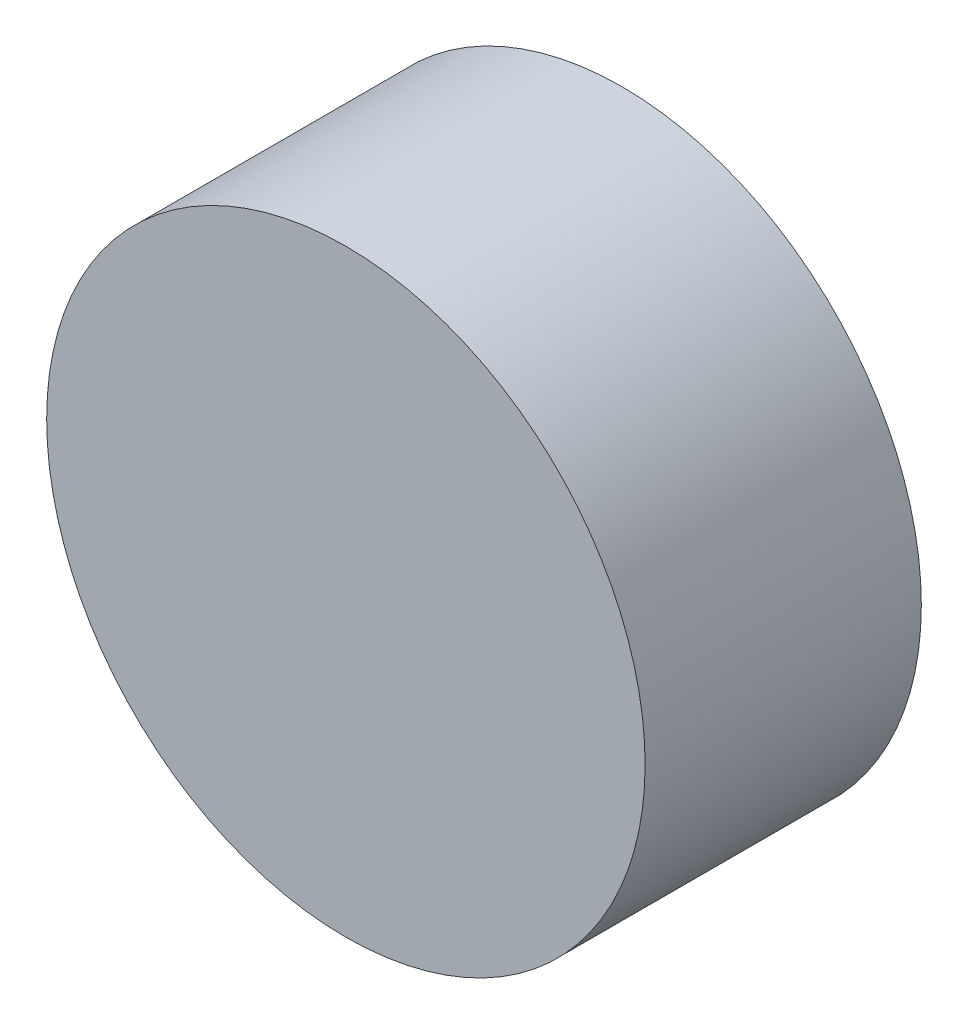
SolidWorks part; units mm, degrees
ref_plane "前视基准面" through (0, 0, 0) normal (0, 0, 1) x (1, 0, 0)
ref_plane "上视基准面" through (0, 0, 0) normal (0, 1, 0) x (1, 0, 0)
ref_plane "右视基准面" through (0, 0, 0) normal (1, 0, 0) x (0, 0, -1)
other "Configuration Table"
sketch "草图1" plane through (0, 0, 0) normal (0, 0, 1) x (1, 0, 0)
  circle A0 centre (0, 0) radius 65
  dimension "D1" = 130
extrude "凸台-拉伸1" add sketch "草图1" along normal blind 60
sketch "草图2" plane through (0, 0, 60) normal (0, 0, 1) x (1, 0, 0)
  circle A0 centre (0, 0) radius 65
